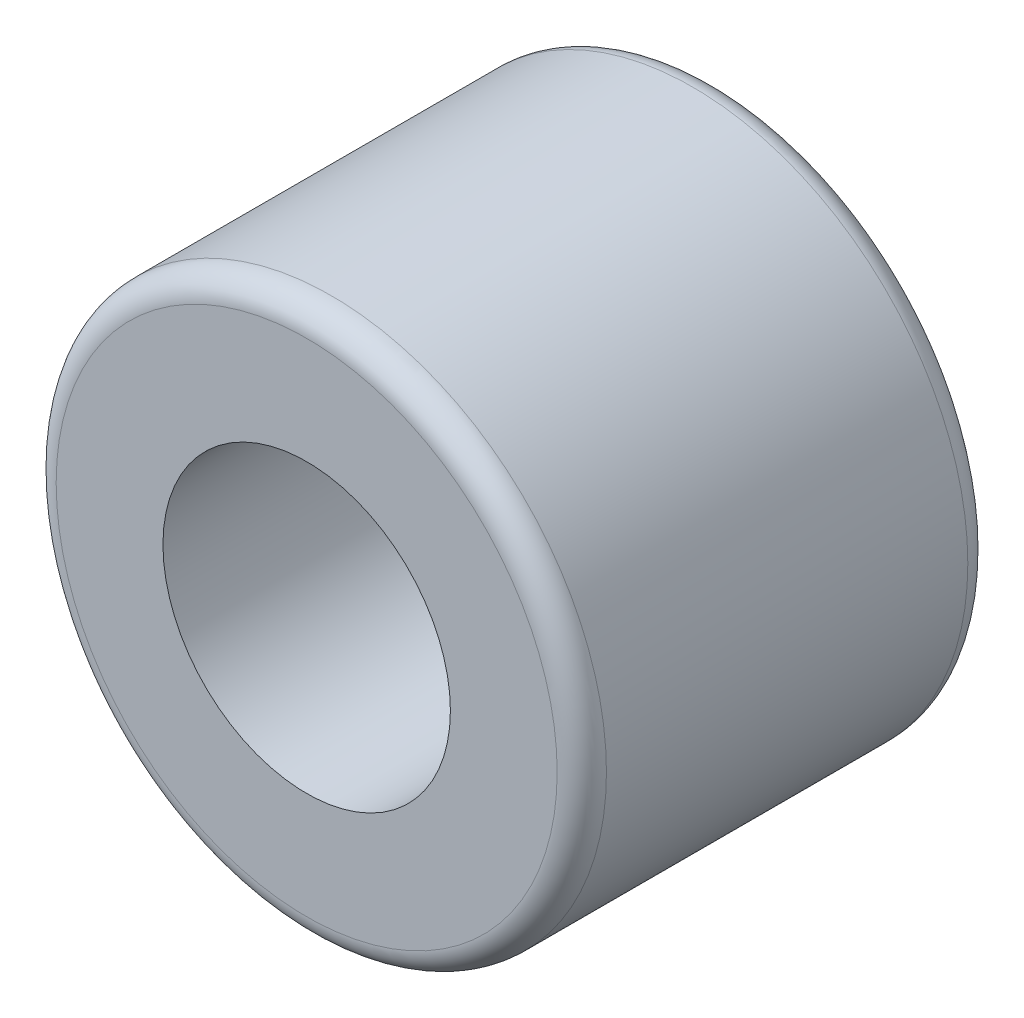
SolidWorks part; units mm, degrees
ref_plane "Front Plane" through (0, 0, 0) normal (0, 0, 1) x (1, 0, 0)
ref_plane "Top Plane" through (0, 0, 0) normal (0, 1, 0) x (1, 0, 0)
ref_plane "Right Plane" through (0, 0, 0) normal (1, 0, 0) x (0, 0, -1)
sketch "Sketch1" plane through (0, 0, 0) normal (0, 0, 1) x (1, 0, 0)
  circle A0 centre (0, 0) radius 8.509
  circle A1 centre (0, 0) radius 4.445
  dimension "D1" = 17.018
  dimension "D2" = 8.89
extrude "Boss-Extrude1" add sketch "Sketch1" along normal blind 12.7
fillet "Fillet2" radius 0.762 2 edges at (8.509, 0, 0) (8.509, 0, 12.7)
